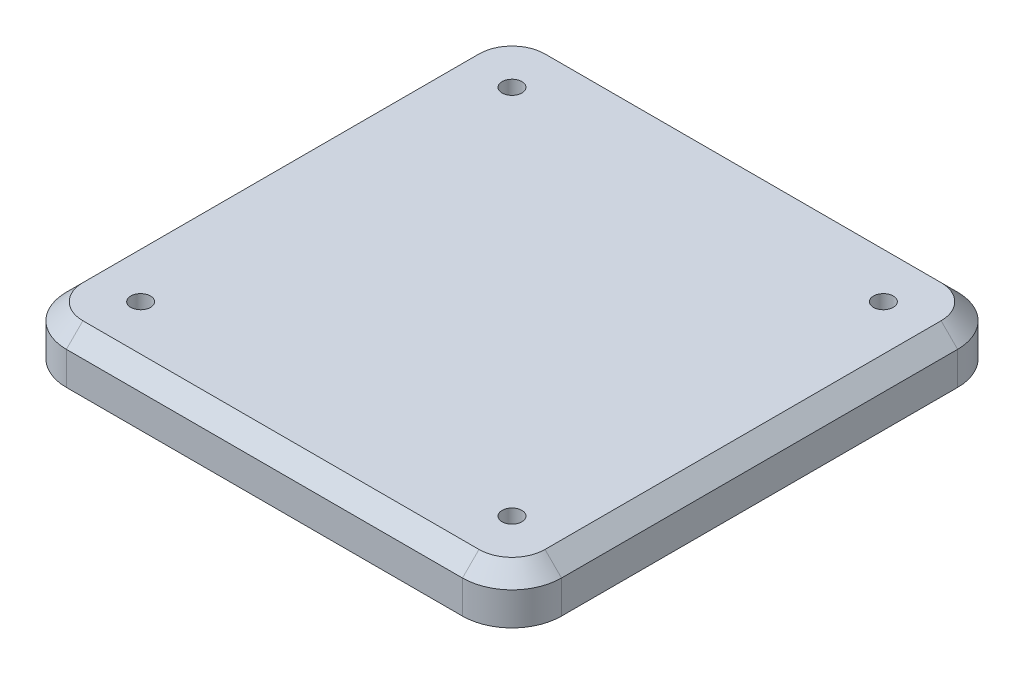
SolidWorks part; units mm, degrees
ref_plane "前基準面" through (0, 0, 0) normal (0, 0, 1) x (1, 0, 0)
ref_plane "上基準面" through (0, 0, 0) normal (0, 1, 0) x (1, 0, 0)
ref_plane "右基準面" through (0, 0, 0) normal (1, 0, 0) x (0, 0, -1)
sketch "草圖1" plane through (0, 0, 0) normal (0, 1, 0) x (1, 0, 0)
  line L1 (0, 0) -> (300, 0)
  line L2 (0, 0) -> (0, 300)
  line L3 (0, 300) -> (300, 300)
  line L4 (300, 0) -> (300, 300)
  dimension "D1" = 300
  dimension "D2" = 300
extrude "填料-伸長1" add sketch "草圖1" along normal blind 30
fillet "圓角1" radius 30 4 edges at (0, 15, -300) (300, 15, -300) (300, 15, 0) (0, 15, 0)
chamfer "導角1" distance 10 angle 45 8 edges at (0, 30, -150) (8.7868, 30, -8.7868) (8.7868, 30, -291.2132) (150, 30, 0) (150, 30, -300) (291.2132, 30, -8.7868) (291.2132, 30, -291.2132) (300, 30, -150)
sketch "草圖2" plane through (0, 0, 0) normal (0, -1, 0) x (1, 0, 0)
  line L0 (30, 0) -> (270, 0) construction
  line L1 (25, -25) -> (275, -25)
  line L2 (25, -25) -> (25, -275)
  line L3 (25, -275) -> (275, -275)
  line L4 (275, -25) -> (275, -275)
  line L5 (270, -300) -> (30, -300) construction
  line L6 (300, -30) -> (300, -270) construction
  line L7 (0, -270) -> (0, -30) construction
  dimension "D1" = 25
  dimension "D2" = 25
  dimension "D3" = 25
  dimension "D4" = 25
sketch "草圖4" plane through (0, 30, 0) normal (0, 1, 0) x (1, 0, 0)
  line L0 (25, 25) -> (25, 275) construction
  line L1 (37.5, 37.5) -> (262.5, 37.5)
  line L2 (37.5, 37.5) -> (37.5, 262.5)
  line L3 (37.5, 262.5) -> (262.5, 262.5)
  line L4 (262.5, 37.5) -> (262.5, 262.5)
  line L5 (25, 25) -> (275, 25) construction
  line L6 (275, 25) -> (275, 275) construction
  line L7 (25, 275) -> (275, 275) construction
  dimension "D1" = 12.5
  dimension "D2" = 12.5
  dimension "D3" = 12.5
  dimension "D4" = 12.5
hole_wizard "Ø20.0mm 定位孔1" positions "3D草圖2" profile "草圖6" hole size "Ø20.0" standard "ISO"
sketch3d "3D草圖2"
  point P0 (37.5, 30, -37.5)
  point P3 (37.5, 30, -262.5)
  point P6 (262.5, 30, -262.5)
  point P9 (262.5, 30, -37.5)
  point P12 (25, 0, -25)
  point P15 (275, 0, -25)
  point P18 (275, 0, -275)
  point P25 (25, 0, -275)
sketch "草圖6" plane through (37.5, 30, -37.5) normal (1, 0, 0) x (0, 0, 1)
  line L0 (0, 0) -> (0, 13.6052)
  line L1 (0, 13.6052) -> (6, 10)
  line L2 (6, 10) -> (6, 0)
  line L5 (6, 0) -> (0, 0)
  line L10 (0, 13.6052) -> (-6, 10) construction
  line L11 (0, -6.35) -> (0, 107.95) construction
  dimension "鑽孔直徑" = 12
  dimension "鑽孔深度" = 10
  dimension "導頭角度" = 118
